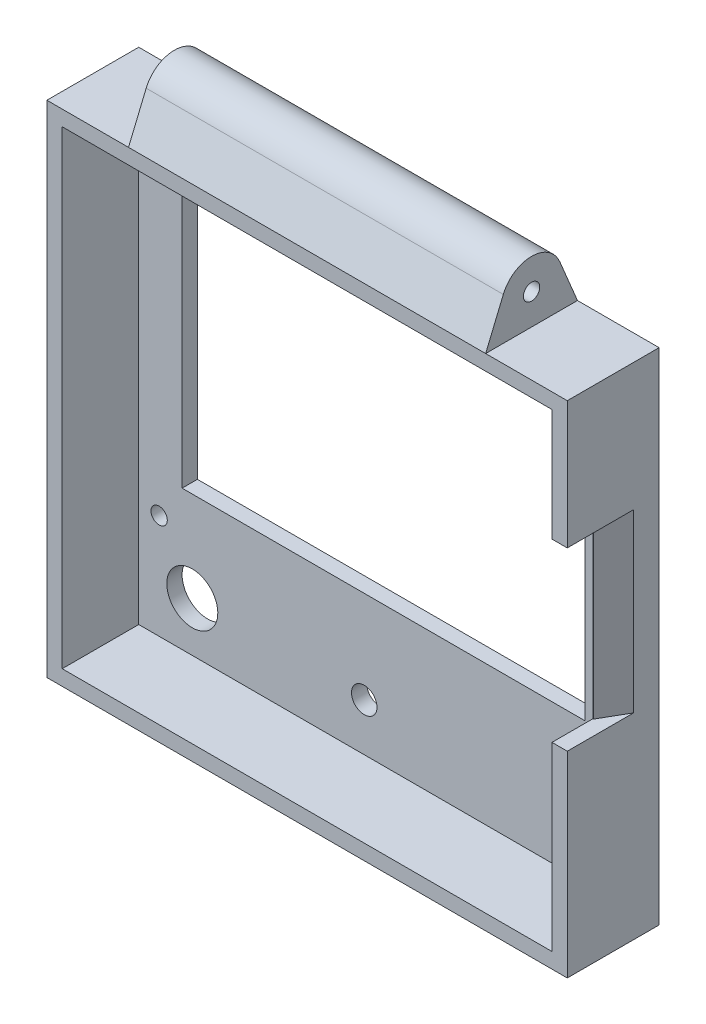
SolidWorks part; units mm, degrees
material "ABS"
ref_plane "Plano frontal" through (0, 0, 0) normal (0, 0, 1) x (1, 0, 0)
ref_plane "Plano superior" through (0, 0, 0) normal (0, 1, 0) x (1, 0, 0)
ref_plane "Plano direito" through (0, 0, 0) normal (1, 0, 0) x (0, 0, -1)
sketch "Esboço2" plane through (0, 0, 0) normal (1, 0, 0) x (0, 0, -1)
  line L0 (0, 0) -> (18, 0)
  line L2 (18, 0) -> (18, 98)
  line L3 (18, 98) -> (0, 98)
  line L4 (0, 98) -> (0, 0)
  point P3 (70.0916, 9.7402)
  point P7 (39.3892, 0)
  point P8 (51.3708, -2.9278)
  point P9 (41.584, 0)
  dimension "D1" = 98
  dimension "D3" = 18
extrude "Ressalto-extrusão1" add sketch "Esboço2" along normal mid plane 102
shell "Casca1" thickness 3
sketch "Esboço4" plane through (0, 0, -18) normal (0, 0, -1) x (1, 0, 0)
  line L0 (51, -98) -> (-51, -98) construction
  line L1 (39.5, -82) -> (-39.5, -82)
  line L2 (39.5, -82) -> (39.5, -30.4)
  line L3 (39.5, -30.4) -> (-39.5, -30.4)
  line L4 (-39.5, -82) -> (-39.5, -30.4)
  line L5 (39.5, -82) -> (-39.5, -30.4) construction
  line L6 (39.5, -30.4) -> (-39.5, -82) construction
  line L8 (44, -23.5) -> (-44, -23.5) construction
  line L9 (44, -23.5) -> (44, -88.5) construction
  line L10 (44, -88.5) -> (-44, -88.5) construction
  line L11 (-44, -23.5) -> (-44, -88.5) construction
  line L12 (44, -23.5) -> (-44, -88.5) construction
  line L13 (44, -88.5) -> (-44, -23.5) construction
  circle A0 centre (-44, -23.5) radius 1.6
  circle A1 centre (-44, -88.5) radius 1.6
  circle A2 centre (44, -88.5) radius 1.6
  circle A3 centre (44, -23.5) radius 1.6
  circle A4 centre (-37.5, -12.7) radius 5
  circle A5 centre (36.75, -15.3) radius 3
  circle A6 centre (-3.8, -12.3) radius 2.5
  point P0 (0, -56.2)
  point P9 (0, -56)
  dimension "D7" = 3.2
  dimension "D11" = 10
  dimension "D14" = 6
  dimension "D16" = 5
  dimension "D1" = 51.6
  dimension "D2" = 79
  dimension "D3" = 16
  dimension "D4" = 65
  dimension "D5" = 88
  dimension "D6" = 6.5
  dimension "D8" = 75.8
  dimension "D9" = 6.5
  dimension "D10" = 7.25
  dimension "D12" = 76.2
  dimension "D13" = 40.2
  dimension "D15" = 8.2
extrude "Corte-extrusão1" cut sketch "Esboço4" against normal up to surface (3 mm away) up to face at (0, 49, -15)
sketch "Esboço5" plane through (51, 0, 0) normal (1, 0, 0) x (0, 0, -1)
  line L0 (14.5385, 106.3077) -> (18, 98)
  line L1 (18, 98) -> (0, 98)
  line L2 (0, 98) -> (3.4615, 106.3077)
  arc A0 (14.5385, 106.3077) -> (3.4615, 106.3077) centre (9, 104) ccw
  circle A1 centre (9, 104) radius 1.6
  point P9 (9, 98)
  dimension "D1" = 12
  dimension "D2" = 3.2
extrude "Ressalto-extrusão2" add sketch "Esboço5" against normal through all
sketch "Esboço6" plane through (0, 0, -18) normal (0, 0, -1) x (-1, 0, 0)
  line L0 (-51, 98) -> (51, 98) construction
  line L1 (-35, 110) -> (35, 110) construction
  line L2 (-35, 98) -> (-35, 110)
  line L3 (35, 98) -> (51, 98)
  line L4 (35, 98) -> (35, 110)
  line L5 (35, 110) -> (51, 110)
  line L6 (-51, 98) -> (-35, 98)
  line L7 (-51, 98) -> (-51, 110)
  line L8 (-51, 110) -> (-35, 110)
  line L9 (51, 98) -> (51, 110)
  line L10 (51, 110) -> (-51, 110) construction
  line L11 (51, 0) -> (51, 98) construction
  point P6 (0, 110)
  point P8 (0, 98)
  point P15 (47.2024, 110)
  point P16 (51, 98)
  point P17 (51, 98)
  dimension "D1" = 70
extrude "Corte-extrusão2" cut sketch "Esboço6" against normal through all
sketch "Esboço7" plane through (51, 0, 0) normal (1, 0, 0) x (0, 0, -1)
  line L0 (0, 98) -> (18, 98) construction
  line L1 (0, 73) -> (8, 73)
  line L2 (0, 73) -> (0, 38.5)
  line L3 (0, 38.5) -> (8, 38.5)
  line L4 (8, 73) -> (8, 38.5)
  line L5 (0, 98) -> (0, 0) construction
  dimension "D1" = 25
  dimension "D2" = 34.5
  dimension "D3" = 8
extrude "Corte-extrusão3" cut sketch "Esboço7" against normal blind 10
chamfer "Chanfro1" distance 5 angle 30 1 edges at (51, 55.75, -8)
